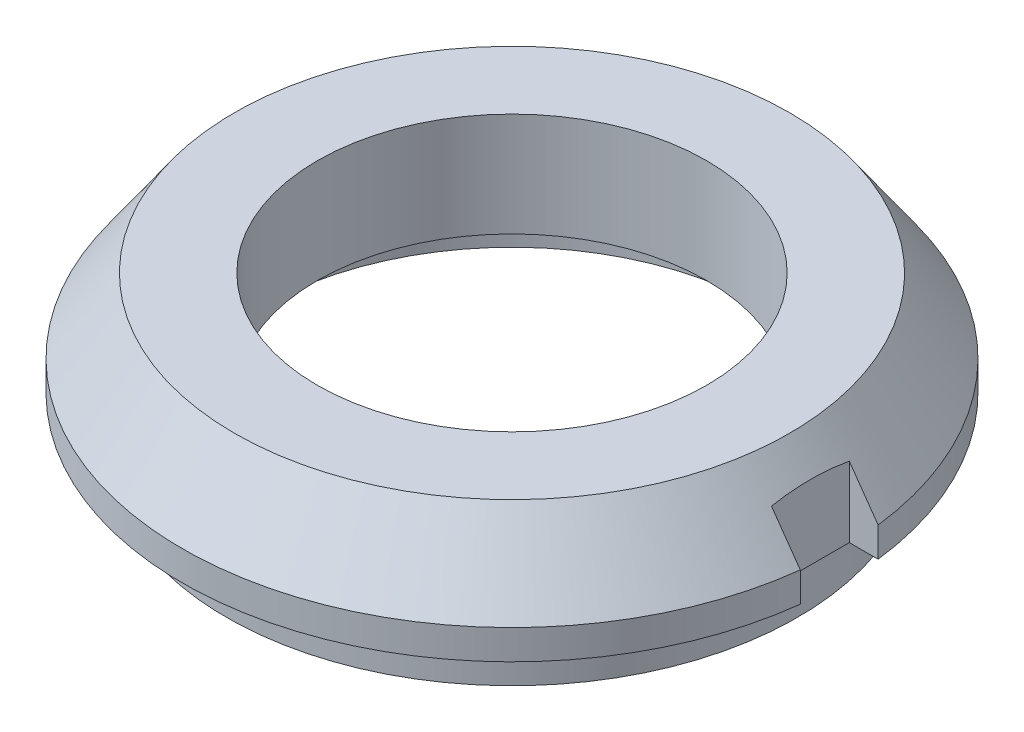
SolidWorks part; units mm, degrees
material "ABS"
ref_plane "Front Plane" through (0, 0, 0) normal (0, 0, 1) x (1, 0, 0)
ref_plane "Top Plane" through (0, 0, 0) normal (0, 1, 0) x (1, 0, 0)
ref_plane "Right Plane" through (0, 0, 0) normal (1, 0, 0) x (0, 0, -1)
sketch "Sketch1" plane through (0, 0, 0) normal (0, 0, 1) x (1, 0, 0)
  line L0 (0, 0) -> (0, 16.1747) construction
  line L1 (-11, 2) -> (-11, -1.1106)
  line L2 (-11, 0) -> (-9.7, 0)
  line L3 (-12.7, 2) -> (-12.7, 3.1437)
  line L4 (-12.7, 2) -> (-11, 2)
  line L5 (-10.5, 2) -> (-7.5, 2) construction
  line L6 (-7.5, 2) -> (-7.5, 6)
  line L7 (-12.7, 0) -> (-12.7, 16.1747) construction
  line L8 (-10.5, 0) -> (-7.5, 0) construction
  line L9 (-10.7, 3.1437) -> (-12.7, 3.1437)
  line L10 (-9.7, 0) -> (-9.7, 2)
  line L11 (-10.7, 6) -> (-10.7, 3.1437)
  line L12 (-7.5, 2) -> (-9.7, 2)
  line L15 (-9.7, 0) -> (-9.7, 16.1747) construction
  line L19 (-12.7, 3.1437) -> (-10.7, 6)
  line L20 (-10.7, 6) -> (-7.5, 6)
  point P4 (-10.5, 16.1747)
  dimension "D4" = 2.8563
  dimension "D5" = 6
  dimension "D6" = 7.5
  dimension "D7" = 9.7
  dimension "D8" = 1.7
  dimension "D9" = 55
  dimension "D10" = 4
  dimension "D11" = 2
  dimension "D12" = 3.2
  dimension "D13" = 12.7
  dimension "D2" = 12.7
  dimension "D3" = 2
revolve "Revolve1" add sketch "Sketch1" angle 360 about L0
sketch "Sketch2" plane through (0, 0, 0) normal (0, 1, 0) x (1, 0, 0)
  line L0 (12.7, 0) -> (-12.7, 0) construction
  line L1 (12.6111, 1.5) -> (-12.7, 1.5)
  line L2 (12.6111, -1.5) -> (-12.7, -1.5)
  line L3 (0, 12.7) -> (0, -1.5)
  line L4 (-11.5, 5.3889) -> (-11.5, -5.3889)
  line L5 (11.5, 5.3889) -> (11.5, -5.3889)
  line L6 (0, 1.5) -> (-12.7, 1.5) construction
  line L7 (0, -1.5) -> (-12.7, -1.5) construction
  line L8 (0, 0) -> (-12.7, 0) construction
  line L9 (-11.5, 12.7) -> (-11.5, -1.5) construction
  line L10 (11.5, 12.7) -> (11.5, -1.5) construction
  circle A0 centre (0, 0) radius 12.7 construction
  circle A1 centre (0, 0) radius 12.7
  dimension "D1" = 1.5
  dimension "D2" = 1.5
  dimension "D3" = 11.5
  dimension "D4" = 11.5
extrude "Cut-Extrude1" cut sketch "Sketch2" along normal through all contours L1 A1 L2 L4 | L2 A1 L1 L5
